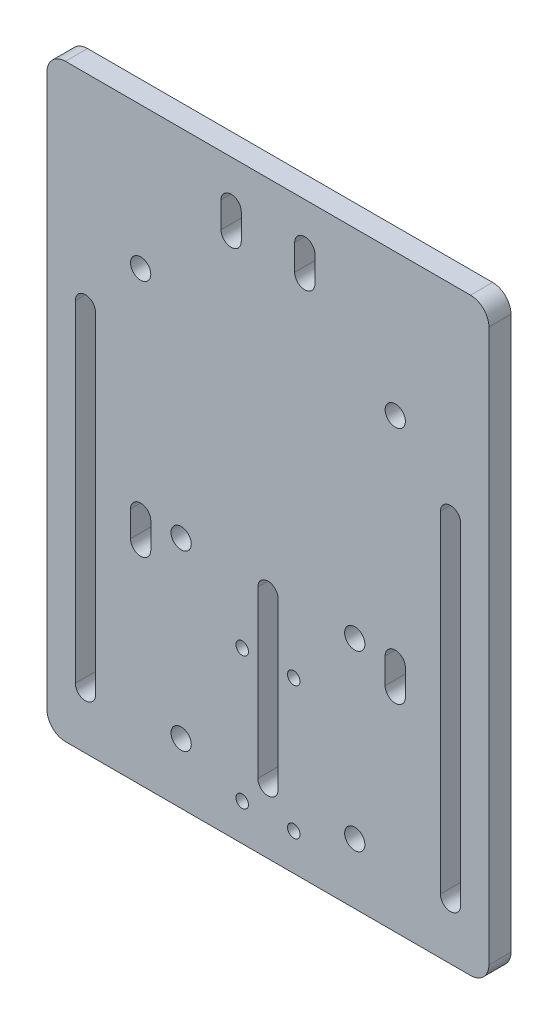
SolidWorks part; units mm, degrees
ref_plane "Front Plane" through (0, 0, 0) normal (0, 0, 1) x (1, 0, 0)
ref_plane "Top Plane" through (0, 0, 0) normal (0, 1, 0) x (1, 0, 0)
ref_plane "Right Plane" through (0, 0, 0) normal (1, 0, 0) x (0, 0, -1)
sketch "Sketch2" plane through (0, 0, 0) normal (0, 0, 1) x (1, 0, 0)
  line L1 (-55, -80) -> (55, -80)
  line L2 (-60, -75) -> (-60, 75)
  line L3 (-55, 80) -> (55, 80)
  line L4 (60, -75) -> (60, 75)
  line L5 (-60, -80) -> (60, 80) construction
  line L6 (-60, 80) -> (60, -80) construction
  arc A0 (55, -80) -> (60, -75) centre (55, -75) ccw
  arc A1 (-55, -80) -> (-60, -75) centre (-55, -75) cw
  arc A2 (55, 80) -> (60, 75) centre (55, 75) cw
  arc A3 (-60, 75) -> (-55, 80) centre (-55, 75) cw
  point P0 (0, 0)
  dimension "D3" = 5
  dimension "D1" = 120
  dimension "D2" = 160
extrude "Boss-Extrude1" add sketch "Sketch2" along normal blind 6
sketch "Sketch3" plane through (0, 0, 6) normal (0, 0, 1) x (1, 0, 0)
  line L0 (0, -17.5) -> (0, -62.5) construction
  line L1 (2.75, -17.5) -> (2.75, -62.5)
  line L2 (-2.75, -17.5) -> (-2.75, -62.5)
  line L3 (-55, -80) -> (55, -80) construction
  arc A0 (2.75, -17.5) -> (-2.75, -17.5) centre (0, -17.5) ccw
  arc A1 (-2.75, -62.5) -> (2.75, -62.5) centre (0, -62.5) ccw
  point P3 (0, -40)
  dimension "D1" = 2.75
  dimension "D2" = 45
  dimension "D3" = 40
extrude "Cut-Extrude1" cut sketch "Sketch3" against normal blind 6
hole_wizard "M5 Clearance Hole1" positions "Sketch4" profile "Sketch5" hole size "M5" standard "ANSI Metric" end condition through all
sketch "Sketch4" plane through (0, 0, 6) normal (0, 0, 1) x (1, 0, 0)
  point P0 (-23.57, -63.57)
  point P2 (-23.57, -16.43)
  point P4 (23.57, -16.43)
  point P6 (23.57, -63.57)
  dimension "D1" = 23.57
  dimension "D2" = 23.57
  dimension "D3" = 23.57
  dimension "D4" = 47.14
sketch "Sketch5" plane through (-23.57, -63.57, 6) normal (1, 0, 0) x (0, -1, 0)
  line L0 (0, 0) -> (0, 6)
  line L1 (0, 6) -> (2.75, 6)
  line L2 (2.75, 6) -> (2.75, 0)
  line L5 (2.75, 0) -> (0, 0)
  line L11 (0, -6.35) -> (0, 107.95) construction
  dimension "Thru Hole Dia." = 5.5
  dimension "Thru Hole Depth" = 6
sketch "Sketch6" plane through (0, 0, 6) normal (0, 0, 1) x (1, 0, 0)
  line L0 (-34.57, -16.43) -> (-34.57, -23.43) construction
  line L1 (-31.82, -16.43) -> (-31.82, -23.43)
  line L2 (-37.32, -16.43) -> (-37.32, -23.43)
  arc A0 (-31.82, -16.43) -> (-37.32, -16.43) centre (-34.57, -16.43) ccw
  arc A1 (-37.32, -23.43) -> (-31.82, -23.43) centre (-34.57, -23.43) ccw
  point P2 (-34.57, -19.93)
  dimension "D1" = 2.75
  dimension "D2" = 7
  dimension "D3" = 11
extrude "Cut-Extrude2" cut sketch "Sketch6" against normal blind 22
hole_wizard "M5 Clearance Hole2" positions "Sketch7" profile "Sketch8" hole size "M5" standard "ANSI Metric" end condition through all
sketch "Sketch7" plane through (0, 0, 6) normal (0, 0, 1) x (1, 0, 0)
  point P0 (-34.57, 41.47)
  dimension "D1" = 61.4
sketch "Sketch8" plane through (-34.57, 41.47, 6) normal (1, 0, 0) x (0, -1, 0)
  line L0 (0, 0) -> (0, 6)
  line L1 (0, 6) -> (2.75, 6)
  line L2 (2.75, 6) -> (2.75, 0)
  line L5 (2.75, 0) -> (0, 0)
  line L11 (0, -6.35) -> (0, 107.95) construction
  dimension "Thru Hole Dia." = 5.5
  dimension "Thru Hole Depth" = 6
sketch "Sketch9" plane through (0, 0, 6) normal (0, 0, 1) x (1, 0, 0)
  line L0 (-49.57, 25.07) -> (-49.57, -64.93) construction
  line L1 (-46.82, 25.07) -> (-46.82, -64.93)
  line L2 (-52.32, 25.07) -> (-52.32, -64.93)
  arc A0 (-46.82, 25.07) -> (-52.32, 25.07) centre (-49.57, 25.07) ccw
  arc A1 (-52.32, -64.93) -> (-46.82, -64.93) centre (-49.57, -64.93) ccw
  point P2 (-49.57, -19.93)
  dimension "D2" = 2.75
  dimension "D1" = 15
  dimension "D3" = 90
extrude "Cut-Extrude3" cut sketch "Sketch9" against normal blind 6
sketch "Sketch10" plane through (0, 0, 6) normal (0, 0, 1) x (1, 0, 0)
  line L0 (0, 85.855) -> (0, -97.3195) construction
mirror "Mirror2" about plane through (0, 0, 0) normal (1, 0, 0) of "Cut-Extrude2", "Cut-Extrude3", "M5 Clearance Hole2"
sketch "Sketch11" plane through (0, 0, 6) normal (0, 0, 1) x (1, 0, 0)
  line L0 (-10, 68.5) -> (-10, 61.5) construction
  line L1 (-7.25, 68.5) -> (-7.25, 61.5)
  line L2 (-12.75, 68.5) -> (-12.75, 61.5)
  line L3 (10, 68.5) -> (10, 61.5) construction
  line L4 (12.75, 68.5) -> (12.75, 61.5)
  line L5 (7.25, 68.5) -> (7.25, 61.5)
  line L9 (55, 80) -> (-55, 80) construction
  arc A0 (-7.25, 68.5) -> (-12.75, 68.5) centre (-10, 68.5) ccw
  arc A1 (-12.75, 61.5) -> (-7.25, 61.5) centre (-10, 61.5) ccw
  arc A2 (12.75, 68.5) -> (7.25, 68.5) centre (10, 68.5) ccw
  arc A3 (7.25, 61.5) -> (12.75, 61.5) centre (10, 61.5) ccw
  point P2 (-10, 65)
  point P7 (10, 65)
  dimension "D1" = 2.75
  dimension "D4" = 10
  dimension "D2" = 7
  dimension "D3" = 20
  dimension "D5" = 15
extrude "Cut-Extrude4" cut sketch "Sketch11" against normal blind 6
hole_wizard "M3 Clearance Hole1" positions "Sketch12" profile "Sketch13" hole size "M3" standard "ANSI Metric"
sketch "Sketch12" plane through (0, 0, 6) normal (0, 0, 1) x (1, 0, 0)
  line L0 (0, 85.855) -> (0, -97.3195) construction
  line L1 (-55, -80) -> (55, -80) construction
  point P0 (-7, -34)
  point P2 (7, -34)
  point P4 (7, -70)
  point P6 (-7, -70)
  dimension "D1" = 7
  dimension "D2" = 14
  dimension "D3" = 36
  dimension "D4" = 10
sketch "Sketch13" plane through (-7, -34, 6) normal (1, 0, 0) x (0, -1, 0)
  line L0 (0, 0) -> (0, 11.0215)
  line L1 (0, 11.0215) -> (1.7, 10)
  line L2 (1.7, 10) -> (1.7, 0)
  line L5 (1.7, 0) -> (0, 0)
  line L10 (0, 11.0215) -> (-1.7, 10) construction
  line L11 (0, -6.35) -> (0, 107.95) construction
  dimension "Hole Dia." = 3.4
  dimension "Hole Depth" = 10
  dimension "Drill Angle" = 118
